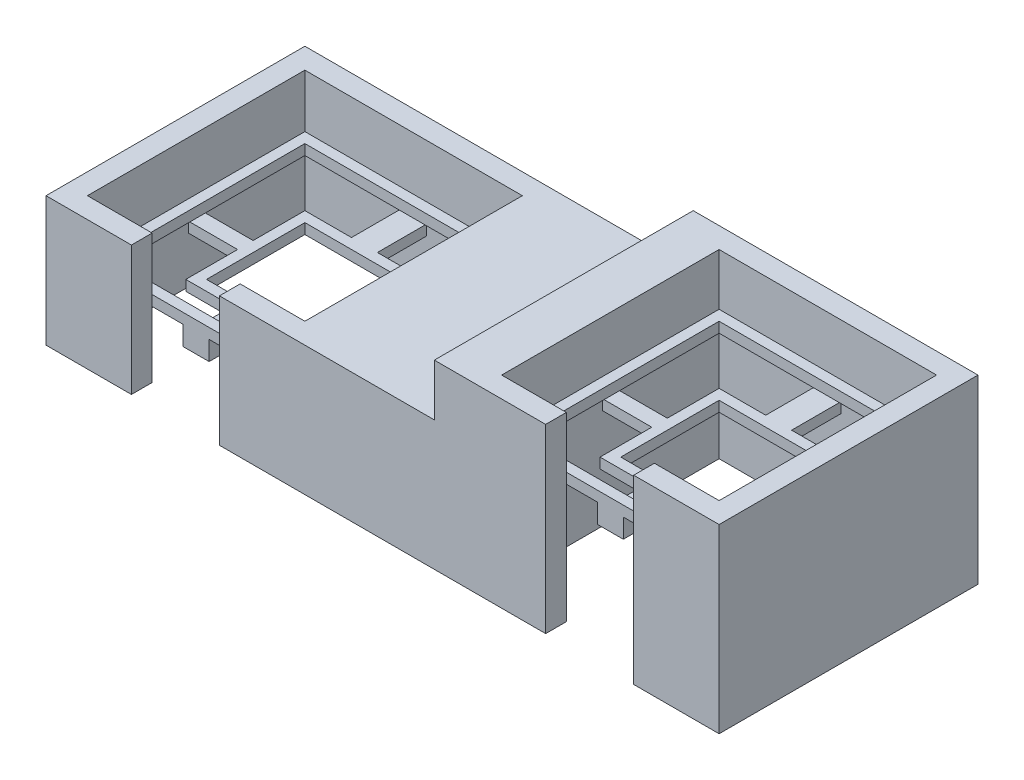
SolidWorks part; units mm, degrees
ref_plane "Front Plane" through (0, 0, 0) normal (0, 0, 1) x (1, 0, 0)
ref_plane "Top Plane" through (0, 0, 0) normal (0, 1, 0) x (1, 0, 0)
ref_plane "Right Plane" through (0, 0, 0) normal (1, 0, 0) x (0, 0, -1)
sketch "Sketch1" plane through (0, 0, 0) normal (0, 1, 0) x (1, 0, 0)
  line L0 (0, 0) -> (80, 0) construction
  line L1 (40, 0) -> (40, 21) construction
  line L2 (-21, 21) -> (21, 21)
  line L3 (-21, 21) -> (-21, -21)
  line L4 (-21, -21) -> (21, -21)
  line L5 (21, 21) -> (21, -21)
  line L6 (-21, 21) -> (21, -21) construction
  line L7 (-21, -21) -> (21, 21) construction
  line L8 (101, -21) -> (59, -21)
  line L9 (59, 21) -> (59, -21)
  line L10 (101, 21) -> (59, 21)
  line L11 (101, 21) -> (101, -21)
  line L12 (-25, 25) -> (-25, -25)
  line L14 (0, 0) -> (0, 21) construction
  line L15 (-25, -25) -> (25, -25)
  line L17 (-25, 25) -> (25, 25)
  line L18 (105, -25) -> (55, -25)
  line L20 (105, 25) -> (55, 25)
  line L21 (105, 25) -> (105, -25)
  line L22 (25, 25) -> (25, -25) construction
  line L23 (55, 25) -> (55, -25) construction
  line L24 (25, 25) -> (55, 25)
  line L25 (25, -25) -> (55, -25)
  dimension "D3" = 4
  dimension "D1" = 80
  dimension "D2" = 42
  dimension "D4" = 4
extrude "Boss-Extrude4" add sketch "Sketch1" along normal blind 10 contours L15 L25 L18 L21 L20 L24 L17 L12 L10 L11 L8 L9 L2 L5 L4 L3
sketch "Sketch5" plane through (0, 0, 25) normal (0, 0, 1) x (1, 0, 0)
  line L0 (-25, 10) -> (105, 10) construction
  line L1 (-8.5, 10) -> (8.5, 10)
  line L2 (-8.5, 10) -> (-8.5, 0)
  line L3 (-8.5, 0) -> (8.5, 0)
  line L4 (8.5, 10) -> (8.5, 0)
  line L5 (-25, 0) -> (105, 0) construction
  line L6 (-25, 10) -> (-25, 0) construction
  line L7 (88.5, 10) -> (71.5, 10)
  line L8 (88.5, 10) -> (88.5, 0)
  line L9 (88.5, 0) -> (71.5, 0)
  line L10 (71.5, 10) -> (71.5, 0)
  line L11 (105, 10) -> (105, 0) construction
  dimension "D1" = 16.5
  dimension "D2" = 16.5
  dimension "D3" = 17
  dimension "D4" = 17
extrude "Cut-Extrude3" cut sketch "Sketch5" against normal up to surface (4 mm away) and the other way through all contours L2 L1 L4 L3 | L8 L7 L10 L9 up to face at (0, 5, 21)
sketch "Sketch6" plane through (0, 10, 0) normal (0, 1, 0) x (1, 0, 0)
  line L0 (40, 25) -> (40, -25)
  line M24 (8.5, -25) -> (71.5, -25)
  line M25 (71.5, -25) -> (71.5, -21)
  line M26 (71.5, -21) -> (59, -21)
  line M27 (59, -21) -> (59, 21)
  line M28 (59, 21) -> (101, 21)
  line M29 (101, 21) -> (101, -21)
  line M30 (101, -21) -> (88.5, -21)
  line M31 (88.5, -21) -> (88.5, -25)
  line M32 (88.5, -25) -> (105, -25)
  line M33 (105, -25) -> (105, 25)
  line M34 (105, 25) -> (-25, 25)
  dimension "D2" = 40
extrude "Boss-Extrude5" add sketch "Sketch6" along normal blind 10 contours L0 M34 M24 M25 M26 M27 M28 M29 M30 M31 M32 M33
sketch "Sketch8" plane through (0, 0, 25) normal (0, 0, 1) x (1, 0, 0)
  line L0 (8.5, 10) -> (40, 10) construction
  line L1 (40, 20) -> (50, 20)
  line L2 (40, 20) -> (40, 10)
  line L3 (40, 10) -> (50, 10)
  line L4 (50, 20) -> (50, 10)
extrude "Cut-Extrude5" cut sketch "Sketch8" against normal through all both and the other way through all
sketch "Sketch9" plane through (0, 0, 0) normal (0, -1, 0) x (1, 0, 0)
  line L64 (-21, 21) -> (-8.5, 21)
  line L65 (-8.5, 21) -> (-8.5, 25)
  line L66 (-8.5, 25) -> (-25, 25)
  line L67 (-25, 25) -> (-25, -25)
  line L70 (-25, -25) -> (105, -25)
  line L71 (105, -25) -> (105, 25)
  line L72 (105, 25) -> (88.5, 25)
  line L73 (88.5, 25) -> (88.5, 21)
  line L74 (88.5, 21) -> (101, 21)
  line L75 (101, 21) -> (101, -21)
  line L76 (101, -21) -> (59, -21)
  line L77 (59, -21) -> (59, 21)
  line L78 (59, 21) -> (71.5, 21)
  line L79 (71.5, 21) -> (71.5, 25)
  line L80 (71.5, 25) -> (8.5, 25)
  line L81 (8.5, 25) -> (8.5, 21)
  line L82 (8.5, 21) -> (21, 21)
  line L83 (21, 21) -> (21, -21)
  line L84 (21, -21) -> (-21, -21)
  line L85 (-21, -21) -> (-21, 21)
  line L86 (-21, 21) -> (-8.5, 21)
  line L87 (-8.5, 21) -> (-8.5, 25)
  line L88 (-8.5, 25) -> (-25, 25)
  line L89 (-25, 25) -> (-25, -25)
  line L90 (-25, -25) -> (105, -25)
  line L91 (105, -25) -> (105, 25)
  line L92 (105, 25) -> (88.5, 25)
  line L93 (88.5, 25) -> (88.5, 21)
  line L94 (88.5, 21) -> (101, 21)
  line L95 (101, 21) -> (101, -21)
  line L96 (101, -21) -> (59, -21)
  line L97 (59, -21) -> (59, 21)
  line L98 (59, 21) -> (71.5, 21)
  line L99 (71.5, 21) -> (71.5, 25)
  line L100 (71.5, 25) -> (8.5, 25)
  line L101 (8.5, 25) -> (8.5, 21)
  line L102 (8.5, 21) -> (21, 21)
  line L103 (21, 21) -> (21, -21)
  line L104 (21, -21) -> (-21, -21)
  line L105 (-21, -21) -> (-21, 21)
  dimension "D1" = 0
extrude "Boss-Extrude6" add sketch "Sketch9" along normal blind 15
sketch "Sketch10" plane through (0, 10, 0) normal (0, 1, 0) x (1, 0, 0)
  line L0 (-19, 19) -> (19, 19)
  line L1 (-21, 21) -> (21, 21)
  line L2 (-21, 21) -> (-21, -21)
  line L3 (-21, -21) -> (21, -21)
  line L4 (21, 21) -> (21, -21)
  line L5 (19, 19) -> (19, -19)
  line L6 (-19, -19) -> (19, -19)
  line L7 (-19, 19) -> (-19, -19)
  dimension "D1" = 2
extrude "Boss-Extrude7" add sketch "Sketch10" against normal blind 2 from offset 10.28 offset against normal yes
sketch "Sketch11" plane through (0, 20, 0) normal (0, 1, 0) x (1, 0, 0)
  line L0 (61, 19) -> (61, -19)
  line L1 (59, 21) -> (101, 21)
  line L2 (59, 21) -> (59, -21)
  line L3 (59, -21) -> (101, -21)
  line L4 (101, 21) -> (101, -21)
  line L5 (61, -19) -> (99, -19)
  line L6 (99, 19) -> (99, -19)
  line L7 (61, 19) -> (99, 19)
  dimension "D1" = 2
extrude "Boss-Extrude8" add sketch "Sketch11" against normal blind 2 from offset 10 offset against normal yes
ref_plane "Plane1" through (0, -4, 0) normal (0, 1, 0) x (1, 0, 0)
sketch "Sketch12" plane through (0, -4, 0) normal (0, 1, 0) x (1, 0, 0)
  line L0 (-19, -19) -> (19, -19) construction
  line L1 (-2.5, 19) -> (2.5, 19)
  line L2 (-2.5, 19) -> (-2.5, 11.5)
  line L3 (-2.5, -19) -> (2.5, -19)
  line L4 (2.5, 19) -> (2.5, 11.5)
  line L5 (-2.5, 19) -> (-1.5132, 11.5) construction
  line L6 (-2.5, -19) -> (-1.5132, -11.5) construction
  line L7 (50, 25) -> (-25, 25) construction
  line L8 (-2.5, 19) -> (2.5, 19)
  line L9 (-2.5, 19) -> (-2.5, 25)
  line L10 (-2.5, 25) -> (2.5, 25)
  line L11 (2.5, 19) -> (2.5, 25)
  line L12 (-8.5, -21) -> (8.5, -21) construction
  line L13 (-2.5, -19) -> (2.5, -19)
  line L14 (-2.5, -19) -> (-2.5, -21)
  line L15 (-2.5, -21) -> (2.5, -21)
  line L16 (2.5, -19) -> (2.5, -21)
  line L17 (-2.5, 9.5) -> (-2.5, -9.5)
  line L18 (-11.5, 11.5) -> (11.5, 11.5)
  line L19 (-11.5, 11.5) -> (-11.5, -11.5)
  line L20 (-11.5, -11.5) -> (11.5, -11.5)
  line L21 (11.5, 11.5) -> (11.5, -11.5)
  line L22 (-11.5, 11.5) -> (11.5, -11.5) construction
  line L23 (-11.5, -11.5) -> (11.5, 11.5) construction
  line L24 (-9.5, 9.5) -> (9.5, 9.5)
  line L25 (-9.5, 9.5) -> (-9.5, -9.5)
  line L26 (-9.5, -9.5) -> (9.5, -9.5)
  line L27 (9.5, 9.5) -> (9.5, -9.5)
  line L28 (-9.5, 9.5) -> (9.5, -9.5) construction
  line L29 (-9.5, -9.5) -> (9.5, 9.5) construction
  line L30 (-1.25, 9.5) -> (1.25, -9.5) construction
  line L31 (1.5132, 11.5) -> (2.5, 19) construction
  line L32 (2.5, 9.5) -> (2.5, -9.5)
  line L33 (-2.5, -11.5) -> (-2.5, -19)
  line L34 (-1.25, -9.5) -> (1.25, 9.5) construction
  line L35 (1.5132, -11.5) -> (2.5, -19) construction
  line L36 (2.5, -11.5) -> (2.5, -19)
  line L37 (19, -19) -> (19, 19) construction
  line L38 (-19, 1.5) -> (-9.5, 1.5)
  line L39 (-19, 1.5) -> (-19, -1.5)
  line L40 (-19, -1.5) -> (-9.5, -1.5)
  line L41 (19, 1.5) -> (19, -1.5)
  line L42 (-19, 1.5) -> (19, -1.5) construction
  line L43 (-19, -1.5) -> (19, 1.5) construction
  line L44 (-2.5, 1.5) -> (2.5, 1.5)
  line L45 (-2.5, -1.5) -> (2.5, -1.5)
  line L46 (9.5, -1.5) -> (19, -1.5)
  line L47 (9.5, 1.5) -> (19, 1.5)
  point P0 (0, 0)
  point P16 (0, 0)
  point P21 (0, 0)
  point P42 (0, 0)
  dimension "D1" = 5
  dimension "D2" = 23
  dimension "D3" = 2
  dimension "D4" = 3
extrude "Boss-Extrude9" add sketch "Sketch12" against normal blind 2 contours L2 L18 L4 L1 | L1 L11 L10 L9 | L21 L18 L19 L20 L24 L27 L26 L25 | L36 L20 L33 L3 | L16 L3 L14 L15 | L39 L40 L19 L38 | L19 L40 L25 L38 | L46 L27 L26 L25 L40 L19 L20 L21 | L47 L27 L46 L21 | L47 L21 L46 L41
sketch "Sketch15" plane through (0, -4, 0) normal (0, 1, 0) x (1, 0, 0)
  line L0 (-2.5, -11.5) -> (-2.5, -21) construction
  line L1 (-2.5, -19) -> (2.5, -19)
  line L2 (-2.5, -19) -> (-2.5, -21)
  line L3 (-2.5, -21) -> (2.5, -21)
  line L4 (2.5, -19) -> (2.5, -21)
  line L5 (-19, -19) -> (19, -19) construction
  line L6 (-8.5, -21) -> (8.5, -21) construction
  line L7 (2.5, -11.5) -> (2.5, -21) construction
extrude "Boss-Extrude12" add sketch "Sketch15" along normal up to surface (1.72 mm away) up to face at (0, -2.28, 0)
sketch "Sketch16" plane through (-19, 0, 0) normal (-1, 0, 0) x (0, 0, 1)
  line L4 (1.5, -4) -> (-1.5, -4)
  line L5 (-1.5, -4) -> (-1.5, -6)
  line L6 (-1.5, -6) -> (1.5, -6)
  line L7 (1.5, -6) -> (1.5, -4)
  line L8 (1.5, -4) -> (-1.5, -4)
  line L9 (-1.5, -4) -> (-1.5, -6)
  line L10 (-1.5, -6) -> (1.5, -6)
  line L11 (1.5, -6) -> (1.5, -4)
  dimension "D1" = 0
extrude "Boss-Extrude13" add sketch "Sketch16" along normal up to surface (2 mm away) up to face at (-21, 4.86, 0)
sketch "Sketch17" plane through (19, 0, 0) normal (1, 0, 0) x (0, 0, -1)
  line L4 (1.5, -4) -> (-1.5, -4)
  line L5 (-1.5, -4) -> (-1.5, -6)
  line L6 (-1.5, -6) -> (1.5, -6)
  line L7 (1.5, -6) -> (1.5, -4)
  line L8 (1.5, -4) -> (-1.5, -4)
  line L9 (-1.5, -4) -> (-1.5, -6)
  line L10 (-1.5, -6) -> (1.5, -6)
  line L11 (1.5, -6) -> (1.5, -4)
  dimension "D1" = 0
extrude "Boss-Extrude14" add sketch "Sketch17" along normal up to surface (2 mm away) up to face at (21, 4.86, 0)
ref_plane "Plane3" through (0, 6.28, 0) normal (0, 1, 0) x (1, 0, 0)
sketch "Sketch19" plane through (0, 6.28, 0) normal (0, 1, 0) x (1, 0, 0)
  line L0 (80, 19) -> (80, -19) construction
  line L1 (99, 19) -> (61, 19) construction
  line L2 (61, -19) -> (99, -19) construction
  line L3 (61, 0) -> (99, 0) construction
  line L4 (61, 19) -> (61, -19) construction
  line L5 (99, -19) -> (99, 19) construction
  line L6 (70.5, 9.5) -> (70.5, -9.5)
  line L7 (68.5, 11.5) -> (91.5, 11.5)
  line L8 (68.5, 11.5) -> (68.5, -11.5)
  line L9 (68.5, -11.5) -> (91.5, -11.5)
  line L10 (91.5, 11.5) -> (91.5, -11.5)
  line L11 (61, 1.5) -> (99, 1.5)
  line L12 (61, 1.5) -> (61, -1.5)
  line L13 (61, -1.5) -> (99, -1.5)
  line L14 (99, 1.5) -> (99, -1.5)
  line L15 (77.5, 19) -> (82.5, 19)
  line L16 (77.5, 19) -> (77.5, -19)
  line L17 (77.5, -19) -> (82.5, -19)
  line L18 (82.5, 19) -> (82.5, -19)
  line L19 (70.5, -9.5) -> (89.5, -9.5)
  line L20 (89.5, 9.5) -> (89.5, -9.5)
  line L21 (70.5, 9.5) -> (89.5, 9.5)
  line L22 (59, 21) -> (59, -21) construction
  line L23 (61, 1.5) -> (59, 1.5)
  line L24 (61, 1.5) -> (61, -1.5)
  line L25 (61, -1.5) -> (59, -1.5)
  line L26 (59, 1.5) -> (59, -1.5)
  line L27 (101, -21) -> (101, 21) construction
  line L28 (99, 1.5) -> (101, 1.5)
  line L29 (99, 1.5) -> (99, -1.5)
  line L30 (99, -1.5) -> (101, -1.5)
  line L31 (101, 1.5) -> (101, -1.5)
  line L32 (101, 21) -> (59, 21) construction
  line L33 (77.5, 19) -> (82.5, 19)
  line L34 (77.5, 19) -> (77.5, 21)
  line L35 (77.5, 21) -> (82.5, 21)
  line L36 (82.5, 19) -> (82.5, 21)
  line L37 (71.5, -21) -> (88.5, -21) construction
  line L38 (77.5, -19) -> (82.5, -19)
  line L39 (77.5, -19) -> (77.5, -21)
  line L40 (77.5, -21) -> (82.5, -21)
  line L41 (82.5, -19) -> (82.5, -21)
  point P24 (99, 0)
  point P25 (80, 19)
  point P26 (68.5, 0)
  point P27 (80, -11.5)
  dimension "D1" = 5
  dimension "D2" = 3
  dimension "D3" = 23
  dimension "D4" = 23
  dimension "D5" = 2
extrude "Boss-Extrude15" add sketch "Sketch19" against normal blind 2 contours L23 L26 L25 L12 | L12 L13 L8 L11 | L19 L6 L13 L8 L9 L16 | L6 L21 L16 L7 L8 L11 | L8 L13 L6 L11 | L16 L21 L18 L7 | L18 L21 L20 L11 L10 L7 | L11 L20 L13 L10 | L13 L20 L19 L18 L9 L10 | L19 L16 L9 L18 | L18 L9 L16 L17 | L41 L17 L39 L40 | L14 L11 L10 L13 | L31 L28 L14 L30 | L18 L15 L16 L7 | L15 L36 L35 L34
sketch "Sketch20" plane through (0, 6.28, 0) normal (0, 1, 0) x (1, 0, 0)
  line L1 (70.5, 9.5) -> (89.5, 9.5)
  line L2 (70.5, 9.5) -> (70.5, -9.5)
  line L3 (70.5, -9.5) -> (89.5, -9.5)
  line L4 (89.5, 9.5) -> (89.5, -9.5)
extrude "Cut-Extrude6" cut sketch "Sketch20" against normal blind 2
sketch "Sketch21" plane through (0, 6.28, 0) normal (0, 1, 0) x (1, 0, 0)
  line L0 (61, -19) -> (99, -19) construction
  line L1 (77.5, -19) -> (82.5, -19)
  line L2 (77.5, -19) -> (77.5, -21)
  line L3 (77.5, -21) -> (82.5, -21)
  line L4 (82.5, -19) -> (82.5, -21)
  line L5 (71.5, -21) -> (88.5, -21) construction
  line L6 (82.5, -11.5) -> (82.5, -21) construction
  line L7 (77.5, -11.5) -> (77.5, -21) construction
extrude "Boss-Extrude16" add sketch "Sketch21" along normal blind 2
